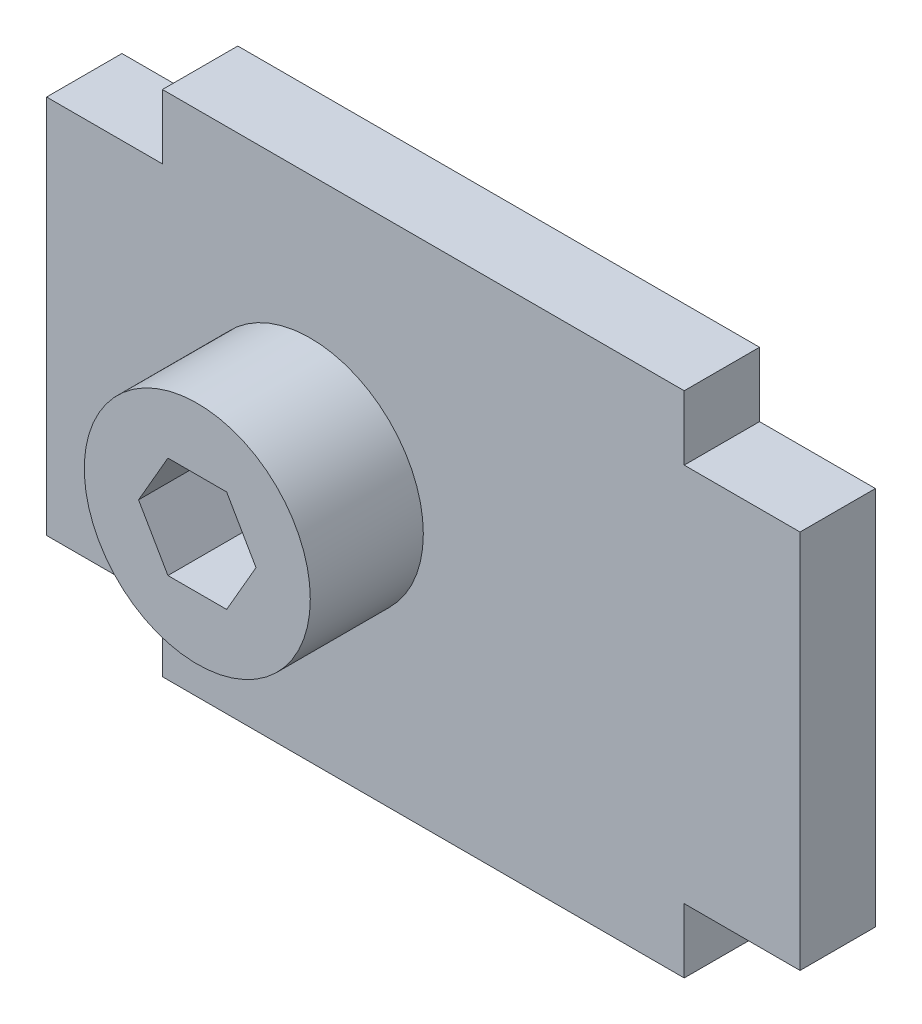
SolidWorks part; units mm, degrees
ref_plane "前视基准面" through (0, 0, 0) normal (0, 0, 1) x (1, 0, 0)
ref_plane "上视基准面" through (0, 0, 0) normal (0, 1, 0) x (1, 0, 0)
ref_plane "右视基准面" through (0, 0, 0) normal (1, 0, 0) x (0, 0, -1)
sketch "草图1" plane through (0, 0, 0) normal (0, 0, 1) x (1, 0, 0)
  line L1 (18.4131, -30.6585) -> (18.4131, -10.1985) construction
  line L2 (58.4131, -10.1985) -> (58.4131, -30.6585) construction
  line L3 (24.4131, -5.4285) -> (52.4131, -5.4285) construction
  line L4 (52.4131, -35.4285) -> (24.4131, -35.4285) construction
  line L24 (58.2631, -10.3485) -> (52.2631, -10.3485)
  line L25 (52.2631, -10.3485) -> (52.2631, -5.5785)
  line L26 (52.2631, -5.5785) -> (24.5631, -5.5785)
  line L27 (24.5631, -5.5785) -> (24.5631, -10.3485)
  line L28 (24.5631, -10.3485) -> (18.5631, -10.3485)
  line L29 (18.5631, -10.3485) -> (18.5631, -30.5085)
  line L30 (18.5631, -30.5085) -> (24.5631, -30.5085)
  line L31 (24.5631, -30.5085) -> (24.5631, -35.2785)
  line L32 (24.5631, -35.2785) -> (52.2631, -35.2785)
  line L33 (52.2631, -35.2785) -> (52.2631, -30.5085)
  line L34 (52.2631, -30.5085) -> (58.2631, -30.5085)
  line L35 (58.2631, -30.5085) -> (58.2631, -10.3485)
  line L36 (58.4131, -10.3485) -> (52.2631, -10.3485)
  line L37 (52.2631, -10.3485) -> (52.2631, -6.9285)
  line L38 (52.2631, -6.9285) -> (24.5631, -6.9285)
  line L39 (24.5631, -6.9285) -> (24.5631, -10.3485)
  line L40 (24.5631, -10.3485) -> (18.4131, -10.3485)
  line L41 (18.4131, -10.3485) -> (18.4131, -30.5085)
  line L42 (18.4131, -30.5085) -> (24.5631, -30.5085)
  line L43 (24.5631, -30.5085) -> (24.5631, -33.9285)
  line L44 (24.5631, -33.9285) -> (52.2631, -33.9285)
  line L45 (52.2631, -33.9285) -> (52.2631, -30.5085)
  line L46 (52.2631, -30.5085) -> (58.4131, -30.5085)
  line L47 (58.4131, -30.5085) -> (58.4131, -10.3485)
  dimension "D2" = 1.5
  dimension "D3" = 1.5
  dimension "D1" = 0.15
extrude "凸台-拉伸1" add sketch "草图1" along normal blind 4
sketch "草图2" plane through (0, 0, 4) normal (0, 0, 1) x (1, 0, 0)
  circle A0 centre (32.4131, -20.4285) radius 1.6
  dimension "D1" = 3.2
extrude "切除-拉伸1" cut sketch "草图2" against normal through all
sketch "草图3" plane through (0, 0, 4) normal (0, 0, 1) x (1, 0, 0)
  line L1 (35.5308, -20.4285) -> (33.9719, -17.7285)
  line L2 (33.9719, -17.7285) -> (30.8543, -17.7285)
  line L3 (30.8543, -17.7285) -> (29.2954, -20.4285)
  line L4 (29.2954, -20.4285) -> (30.8543, -23.1285)
  line L5 (30.8543, -23.1285) -> (33.9719, -23.1285)
  line L6 (33.9719, -23.1285) -> (35.5308, -20.4285)
  circle A0 centre (32.4131, -20.4285) radius 6
  circle A1 centre (32.4131, -20.4285) radius 2.7 construction
  dimension "D2" = 12
  dimension "D1" = 5.4
extrude "凸台-拉伸2" add sketch "草图3" along normal blind 6 contours A0 L6 L5 L4 L3 L2 L1
